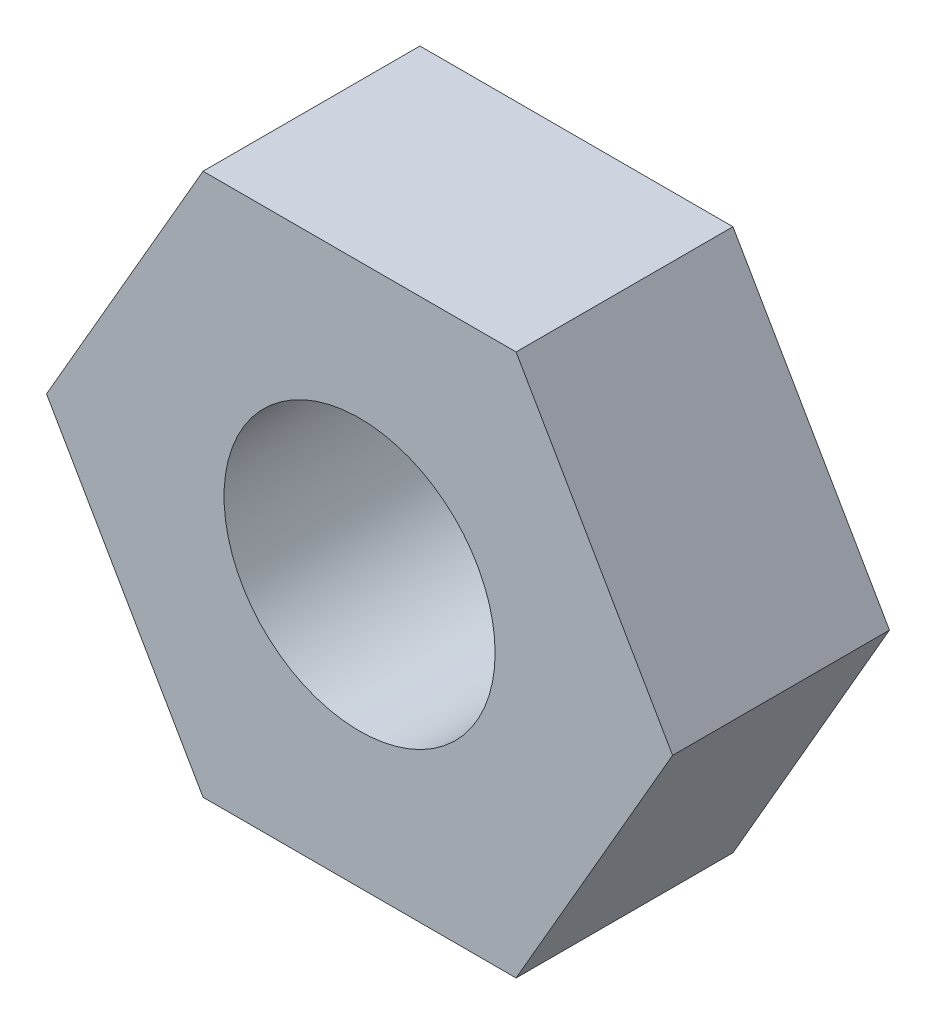
SolidWorks part; units mm, degrees
ref_plane "Front Plane" through (0, 0, 0) normal (0, 0, 1) x (1, 0, 0)
ref_plane "Top Plane" through (0, 0, 0) normal (0, 1, 0) x (1, 0, 0)
ref_plane "Right Plane" through (0, 0, 0) normal (1, 0, 0) x (0, 0, -1)
sketch "Sketch1" plane through (0, 0, 0) normal (0, 0, 1) x (1, 0, 0)
  line L0 (2.3094, 0) -> (1.1547, 2)
  line L1 (1.1547, 2) -> (-1.1547, 2)
  line L2 (-1.1547, 2) -> (-2.3094, 0)
  line L3 (-2.3094, 0) -> (-1.1547, -2)
  line L4 (-1.1547, -2) -> (1.1547, -2)
  line L5 (1.1547, -2) -> (2.3094, 0)
  circle A0 centre (0, 0) radius 1
extrude "Nut_Envelope" add sketch "Sketch1" along normal blind 1.6
